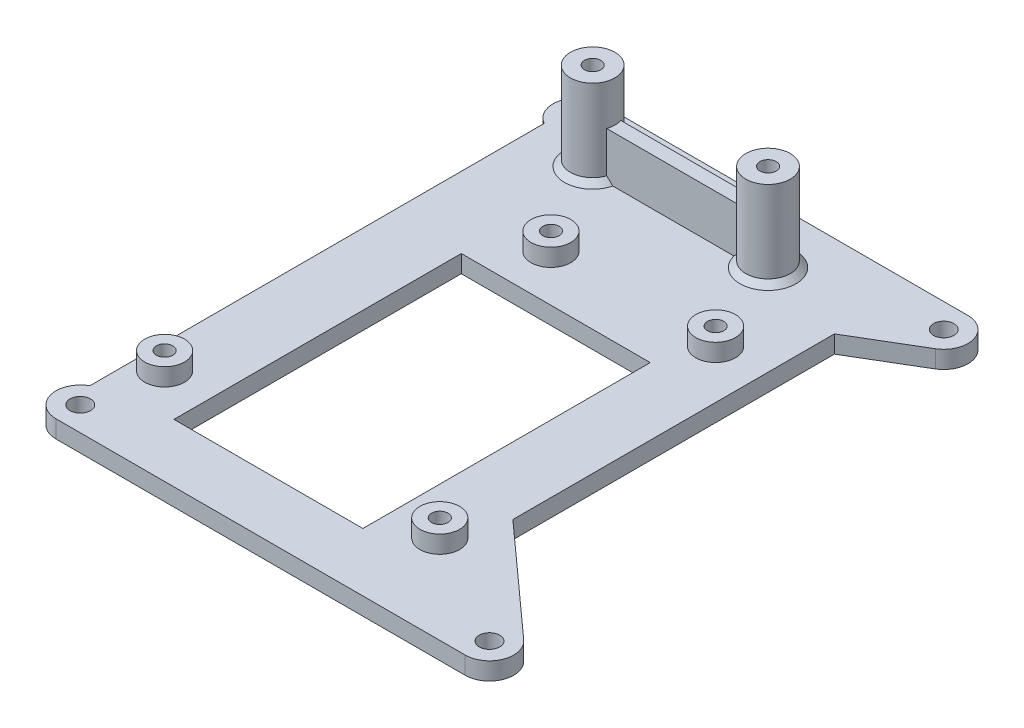
SolidWorks part; units mm, degrees
material "S235JR"
ref_plane "Piano X" through (0, 0, 0) normal (0, 0, 1) x (1, 0, 0)
ref_plane "Piano Y" through (0, 0, 0) normal (0, 1, 0) x (1, 0, 0)
ref_plane "Piano Z" through (0, 0, 0) normal (1, 0, 0) x (0, 0, -1)
sketch "Schizzo1" plane through (0, 0, 0) normal (0, 1, 0) x (1, 0, 0)
  line L4 (-72, 3.6363) -> (-72, 81.3637)
  line L5 (2.7777, 3.0833) -> (-16, 20)
  line L6 (-16, 75) -> (-5.1793, 81.4328)
  line L8 (0, -4.15) -> (-70, -4.15)
  line L11 (-70, 89.15) -> (-7.3, 89.15)
  line L12 (-16, 20) -> (-16, 75)
  line L13 (-70, 85) -> (-7.3, 85) construction
  line L14 (-70, 85) -> (-70, 0) construction
  line L15 (-70, 0) -> (0, 0) construction
  line L17 (-52.49, 63) -> (-24.32, 63) construction
  line L18 (-67.82, 12.25) -> (-67.82, 11) construction
  line L19 (-43.66, 11) -> (-43.66, 63) construction
  line L24 (-67.82, 11) -> (-19.5, 11) construction
  arc A0 (0, -4.15) -> (2.7777, 3.0833) centre (0, 0) ccw
  arc A1 (-5.1793, 81.4328) -> (-7.3, 89.15) centre (-7.3, 85) ccw
  arc A2 (-70, -4.15) -> (-72, 3.6363) centre (-70, 0) cw
  arc A3 (-72, 81.3637) -> (-70, 89.15) centre (-70, 85) cw
  circle A4 centre (-67.82, 12.25) radius 1.4
  circle A5 centre (-19.5, 11) radius 1.4
  circle A6 centre (-24.32, 63) radius 1.4
  circle A7 centre (-52.49, 63) radius 1.4
  circle A8 centre (0, 0) radius 1.75
  circle A9 centre (-70, 0) radius 1.75
  circle A10 centre (-70, 85) radius 1.75
  circle A11 centre (-7.3, 85) radius 1.75
  dimension "D4" = 2.8
  dimension "D6" = 3.5
  dimension "D1" = 70
  dimension "D3" = 56
  dimension "D7" = 85
  dimension "D10" = 16
  dimension "D8" = 28.17
  dimension "D12" = 4.82
  dimension "D9" = 48.32
  dimension "D11" = 1.25
  dimension "D13" = 52
  dimension "D14" = 11
  dimension "D15" = 3.5
  dimension "D2" = 7.3
  dimension "D16" = 20
  dimension "D17" = 10
  dimension "D5" = 2.4
extrude "Estrusione-Estrusione1" add sketch "Schizzo1" along normal blind 3
sketch "Schizzo2" plane through (0, 3, 0) normal (0, 1, 0) x (1, 0, 0)
  circle A0 centre (-67.82, 12.25) radius 3.4
  circle A1 centre (-19.5, 11) radius 3.4
  circle A2 centre (-24.32, 63) radius 3.4
  circle A3 centre (-52.49, 63) radius 3.4
  circle A4 centre (-19.5, 11) radius 1.4 construction
  circle A5 centre (-67.82, 12.25) radius 1.4 construction
  circle A6 centre (-24.32, 63) radius 1.4 construction
  circle A7 centre (-52.49, 63) radius 1.4 construction
  circle A8 centre (-19.5, 11) radius 1.4
  circle A9 centre (-67.82, 12.25) radius 1.4
  circle A10 centre (-24.32, 63) radius 1.4
  circle A11 centre (-52.49, 63) radius 1.4
  dimension "D1" = 2
extrude "Estrusione-Estrusione2" add sketch "Schizzo2" along normal blind 3
sketch "Schizzo3" plane through (0, 3, 0) normal (0, 1, 0) x (1, 0, 0)
  line L0 (-61.5, 79.15) -> (-31.5, 79.15) construction
  line L1 (-46.5, 79.15) -> (-46.5, 89.15) construction
  line L2 (-7.3, 89.15) -> (-70, 89.15) construction
  circle A0 centre (-61.5, 79.15) radius 3.8
  circle A1 centre (-31.5, 79.15) radius 3.8
  circle A3 centre (-31.5, 79.15) radius 1.4 construction
  circle A4 centre (-70, 85) radius 1.75 construction
  dimension "D5" = 2.8
  dimension "D2" = 10
  dimension "D4" = 30
  dimension "D1" = 2.4
  dimension "D3" = 8.5
extrude "Estrusione-Estrusione3" add sketch "Schizzo3" along normal blind 15
hole_wizard "Foro Ø2.8 (2.8)-1" positions "Schizzo4" profile "Schizzo5" hole size "Ø2.8" standard "ISO"
sketch "Schizzo4" plane through (0, 18, 0) normal (0, 1, 0) x (1, 0, 0)
  point P0 (-61.5, 79.15)
  point P3 (-31.5, 79.15)
sketch "Schizzo5" plane through (-61.5, 18, -79.15) normal (1, 0, 0) x (0, 0, 1)
  line L0 (0, 0) -> (0, 10)
  line L1 (0, 10) -> (1.4, 10)
  line L2 (1.4, 10) -> (1.4, 0)
  line L5 (1.4, 0) -> (0, 0)
  line L10 (0, 10) -> (-1.4, 10) construction
  line L11 (0, -6.35) -> (0, 107.95) construction
  dimension "Hole Dia." = 2.8
  dimension "Hole Depth" = 10
  dimension "Drill Angle" = 180
sketch "Schizzo6" plane through (0, 3, 0) normal (0, 1, 0) x (1, 0, 0)
  line L1 (-57.8944, 80.35) -> (-35.1056, 80.35)
  line L2 (-57.8944, 80.35) -> (-57.8944, 77.95)
  line L3 (-57.8944, 77.95) -> (-35.1056, 77.95)
  line L4 (-35.1056, 80.35) -> (-35.1056, 77.95)
  circle A0 centre (-31.5, 79.15) radius 3.8 construction
  circle A1 centre (-61.5, 79.15) radius 3.8 construction
  circle A2 centre (-31.5, 79.15) radius 3.8 construction
  dimension "D1" = 2.4
extrude "Estrusione-Estrusione4" add sketch "Schizzo6" along normal blind 8
chamfer "Smusso1" distance 1 angle 45 2 edges at (-65.3, 3, -79.15) (-27.7, 3, -79.15)
sketch "Schizzo8" plane through (0, 3, 0) normal (0, 1, 0) x (1, 0, 0)
  line L0 (-70, -4.15) -> (0, -4.15) construction
  line L1 (-59.82, 55) -> (-27.5, 55)
  line L2 (-59.82, 55) -> (-59.82, 5.85)
  line L3 (-59.82, 5.85) -> (-27.5, 5.85)
  line L4 (-27.5, 55) -> (-27.5, 5.85)
  circle A0 centre (-19.5, 11) radius 3.4 construction
  circle A1 centre (-67.82, 12.25) radius 3.4 construction
  circle A2 centre (-52.49, 63) radius 3.4 construction
  dimension "D1" = 10
  dimension "D2" = 8
  dimension "D3" = 8
  dimension "D4" = 8
extrude "Taglio-Estrusione1" cut sketch "Schizzo8" against normal through all
equation "\"D1@Schizzo2\"=0.4*5"
equation "\"D1@Schizzo3\"=0.4*6"
equation "\"D5@Schizzo1\"=0.4*6"
